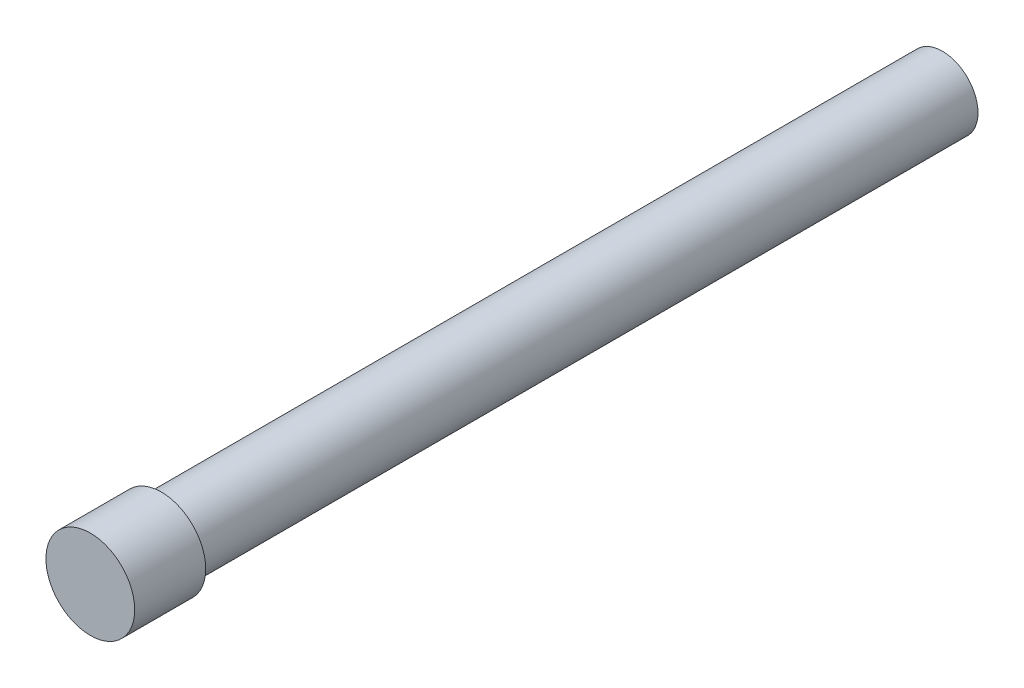
SolidWorks part; units mm, degrees
ref_plane "Front" through (0, 0, 0) normal (0, 0, 1) x (1, 0, 0)
ref_plane "Top" through (0, 0, 0) normal (0, 1, 0) x (1, 0, 0)
ref_plane "Right" through (0, 0, 0) normal (1, 0, 0) x (0, 0, -1)
sketch "Croquis1" plane through (0, 0, 0) normal (0, 0, 1) x (1, 0, 0)
  circle A0 centre (0, 0) radius 1
  dimension "D1" = 2
extrude "Saliente-Extruir1" add sketch "Croquis1" along normal blind 22
sketch "Croquis2" plane through (0, 0, 22) normal (0, 0, 1) x (1, 0, 0)
  circle A0 centre (0, 0) radius 1.25
  dimension "D1" = 2.5
extrude "Saliente-Extruir2" add sketch "Croquis2" along normal blind 2
